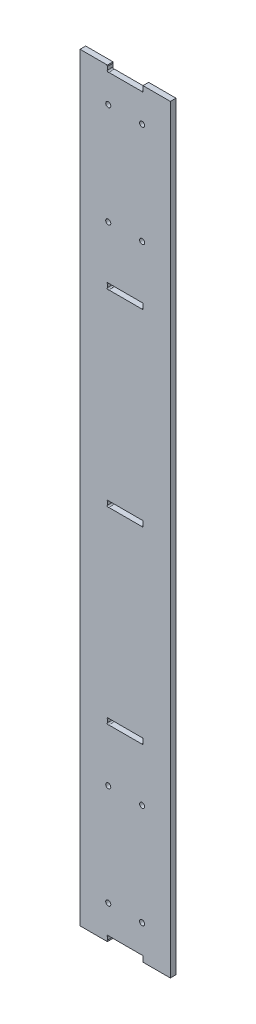
SolidWorks part; units mm, degrees
material "Acrylic (Medium-high impact)"
ref_plane "Front Plane" through (0, 0, 0) normal (0, 0, 1) x (1, 0, 0)
ref_plane "Top Plane" through (0, 0, 0) normal (0, 1, 0) x (1, 0, 0)
ref_plane "Right Plane" through (0, 0, 0) normal (1, 0, 0) x (0, 0, -1)
sketch "Sketch1" plane through (0, 0, 0) normal (0, 1, 0) x (1, 0, 0)
  line L0 (0, 0) -> (0, 76.2) construction
  line L2 (25.4, 68.667) -> (-25.4, 68.667)
  line L3 (25.4, 68.667) -> (25.4, 71.842)
  line L4 (25.4, 71.842) -> (-25.4, 71.842)
  line L5 (-25.4, 68.667) -> (-25.4, 71.842)
  line L6 (25.4, 68.667) -> (-25.4, 71.842) construction
  line L7 (25.4, 71.842) -> (-25.4, 68.667) construction
  circle A0 centre (0, 0) radius 76.2 construction
  point P4 (0, 70.2545)
  dimension "D1" = 152.4
  dimension "D2" = 3.175
  dimension "D3" = 50.8
extrude "Boss-Extrude1" add sketch "Sketch1" along normal blind 427.1518
sketch "Sketch2" plane through (0, 0, -68.667) normal (0, 0, 1) x (1, 0, 0)
  line L1 (-25.4, 427.1518) -> (25.4, 427.1518)
  line L2 (-25.4, 427.1518) -> (-25.4, 0)
  line L3 (-25.4, 0) -> (25.4, 0)
  line L4 (25.4, 427.1518) -> (25.4, 0)
sketch "Sketch3" plane through (0, 0, -68.667) normal (0, 0, 1) x (1, 0, 0)
  line L0 (0, 427.1518) -> (0, 0) construction
  line L1 (-25.4, 427.1518) -> (25.4, 427.1518) construction
  line L2 (-25.4, 0) -> (25.4, 0) construction
  line L3 (-25.4, 213.5759) -> (25.4, 213.5759) construction
  line L4 (-25.4, 427.1518) -> (-25.4, 0) construction
  line L5 (25.4, 427.1518) -> (25.4, 0) construction
  circle A0 centre (-19.05, 376.3518) radius 1.4224
  circle A1 centre (-12.7, 376.3518) radius 1.4224
  circle A2 centre (-6.35, 376.3518) radius 1.4224
  circle A3 centre (0, 376.3518) radius 1.4224
  circle A4 centre (6.35, 376.3518) radius 1.4224
  circle A5 centre (12.7, 376.3518) radius 1.4224
  circle A6 centre (19.05, 376.3518) radius 1.4224
  circle A7 centre (-12.7, 370.0018) radius 1.4224
  circle A8 centre (-6.35, 370.0018) radius 1.4224
  circle A9 centre (0, 370.0018) radius 1.4224
  circle A10 centre (6.35, 370.0018) radius 1.4224
  circle A11 centre (12.7, 370.0018) radius 1.4224
  circle A12 centre (19.05, 370.0018) radius 1.4224
  circle A13 centre (-12.7, 363.6518) radius 1.4224
  circle A14 centre (-6.35, 363.6518) radius 1.4224
  circle A15 centre (0, 363.6518) radius 1.4224
  circle A16 centre (6.35, 363.6518) radius 1.4224
  circle A17 centre (12.7, 363.6518) radius 1.4224
  circle A18 centre (19.05, 363.6518) radius 1.4224
  circle A19 centre (-12.7, 357.3018) radius 1.4224
  circle A20 centre (-6.35, 357.3018) radius 1.4224
  circle A21 centre (0, 357.3018) radius 1.4224
  circle A22 centre (6.35, 357.3018) radius 1.4224
  circle A23 centre (12.7, 357.3018) radius 1.4224
  circle A24 centre (19.05, 357.3018) radius 1.4224
  circle A25 centre (-12.7, 350.9518) radius 1.4224
  circle A26 centre (-6.35, 350.9518) radius 1.4224
  circle A27 centre (0, 350.9518) radius 1.4224
  circle A28 centre (6.35, 350.9518) radius 1.4224
  circle A29 centre (12.7, 350.9518) radius 1.4224
  circle A30 centre (19.05, 350.9518) radius 1.4224
  circle A31 centre (-12.7, 344.6018) radius 1.4224
  circle A32 centre (-6.35, 344.6018) radius 1.4224
  circle A33 centre (0, 344.6018) radius 1.4224
  circle A34 centre (6.35, 344.6018) radius 1.4224
  circle A35 centre (12.7, 344.6018) radius 1.4224
  circle A36 centre (19.05, 344.6018) radius 1.4224
  circle A37 centre (-12.7, 338.2518) radius 1.4224
  circle A38 centre (-6.35, 338.2518) radius 1.4224
  circle A39 centre (0, 338.2518) radius 1.4224
  circle A40 centre (6.35, 338.2518) radius 1.4224
  circle A41 centre (12.7, 338.2518) radius 1.4224
  circle A42 centre (19.05, 338.2518) radius 1.4224
  circle A43 centre (-12.7, 331.9018) radius 1.4224
  circle A44 centre (-6.35, 331.9018) radius 1.4224
  circle A45 centre (0, 331.9018) radius 1.4224
  circle A46 centre (6.35, 331.9018) radius 1.4224
  circle A47 centre (12.7, 331.9018) radius 1.4224
  circle A48 centre (19.05, 331.9018) radius 1.4224
  circle A49 centre (-19.05, 370.0018) radius 1.4224
  circle A50 centre (-19.05, 363.6518) radius 1.4224
  circle A51 centre (-19.05, 357.3018) radius 1.4224
  circle A52 centre (-19.05, 350.9518) radius 1.4224
  circle A53 centre (-19.05, 344.6018) radius 1.4224
  circle A54 centre (-19.05, 338.2518) radius 1.4224
  circle A55 centre (-19.05, 331.9018) radius 1.4224
  circle A56 centre (-19.05, 325.5518) radius 1.4224
  circle A57 centre (-12.7, 325.5518) radius 1.4224
  circle A58 centre (-6.35, 325.5518) radius 1.4224
  circle A59 centre (0, 325.5518) radius 1.4224
  circle A60 centre (6.35, 325.5518) radius 1.4224
  circle A61 centre (12.7, 325.5518) radius 1.4224
  circle A62 centre (19.05, 325.5518) radius 1.4224
  circle A63 centre (-19.05, 319.2018) radius 1.4224
  circle A64 centre (-12.7, 319.2018) radius 1.4224
  circle A65 centre (-6.35, 319.2018) radius 1.4224
  circle A66 centre (0, 319.2018) radius 1.4224
  circle A67 centre (6.35, 319.2018) radius 1.4224
  circle A68 centre (12.7, 319.2018) radius 1.4224
  circle A69 centre (19.05, 319.2018) radius 1.4224
  circle A70 centre (-19.05, 312.8518) radius 1.4224
  circle A71 centre (-12.7, 312.8518) radius 1.4224
  circle A72 centre (-6.35, 312.8518) radius 1.4224
  circle A73 centre (0, 312.8518) radius 1.4224
  circle A74 centre (6.35, 312.8518) radius 1.4224
  circle A75 centre (12.7, 312.8518) radius 1.4224
  circle A76 centre (19.05, 312.8518) radius 1.4224
  circle A77 centre (-19.05, 306.5018) radius 1.4224
  circle A78 centre (-12.7, 306.5018) radius 1.4224
  circle A79 centre (-6.35, 306.5018) radius 1.4224
  circle A80 centre (0, 306.5018) radius 1.4224
  circle A81 centre (6.35, 306.5018) radius 1.4224
  circle A82 centre (12.7, 306.5018) radius 1.4224
  circle A83 centre (19.05, 306.5018) radius 1.4224
  circle A84 centre (-19.05, 300.1518) radius 1.4224
  circle A85 centre (-12.7, 300.1518) radius 1.4224
  circle A86 centre (-6.35, 300.1518) radius 1.4224
  circle A87 centre (0, 300.1518) radius 1.4224
  circle A88 centre (6.35, 300.1518) radius 1.4224
  circle A89 centre (12.7, 300.1518) radius 1.4224
  circle A90 centre (19.05, 300.1518) radius 1.4224
  circle A91 centre (-19.05, 293.8018) radius 1.4224
  circle A92 centre (-12.7, 293.8018) radius 1.4224
  circle A93 centre (-6.35, 293.8018) radius 1.4224
  circle A94 centre (0, 293.8018) radius 1.4224
  circle A95 centre (6.35, 293.8018) radius 1.4224
  circle A96 centre (12.7, 293.8018) radius 1.4224
  circle A97 centre (19.05, 293.8018) radius 1.4224
  circle A98 centre (-19.05, 287.4518) radius 1.4224
  circle A99 centre (-12.7, 287.4518) radius 1.4224
  circle A100 centre (-6.35, 287.4518) radius 1.4224
  circle A101 centre (0, 287.4518) radius 1.4224
  circle A102 centre (6.35, 287.4518) radius 1.4224
  circle A103 centre (12.7, 287.4518) radius 1.4224
  circle A104 centre (19.05, 287.4518) radius 1.4224
  circle A105 centre (19.05, 139.7) radius 1.4224
  circle A106 centre (12.7, 139.7) radius 1.4224
  circle A107 centre (6.35, 139.7) radius 1.4224
  circle A108 centre (0, 139.7) radius 1.4224
  circle A109 centre (-6.35, 139.7) radius 1.4224
  circle A110 centre (-12.7, 139.7) radius 1.4224
  circle A111 centre (-19.05, 139.7) radius 1.4224
  circle A112 centre (19.05, 133.35) radius 1.4224
  circle A113 centre (12.7, 133.35) radius 1.4224
  circle A114 centre (6.35, 133.35) radius 1.4224
  circle A115 centre (0, 133.35) radius 1.4224
  circle A116 centre (-6.35, 133.35) radius 1.4224
  circle A117 centre (-12.7, 133.35) radius 1.4224
  circle A118 centre (-19.05, 133.35) radius 1.4224
  circle A119 centre (19.05, 127) radius 1.4224
  circle A120 centre (12.7, 127) radius 1.4224
  circle A121 centre (6.35, 127) radius 1.4224
  circle A122 centre (0, 127) radius 1.4224
  circle A123 centre (-6.35, 127) radius 1.4224
  circle A124 centre (-12.7, 127) radius 1.4224
  circle A125 centre (-19.05, 127) radius 1.4224
  circle A126 centre (19.05, 120.65) radius 1.4224
  circle A127 centre (12.7, 120.65) radius 1.4224
  circle A128 centre (6.35, 120.65) radius 1.4224
  circle A129 centre (0, 120.65) radius 1.4224
  circle A130 centre (-6.35, 120.65) radius 1.4224
  circle A131 centre (-12.7, 120.65) radius 1.4224
  circle A132 centre (-19.05, 120.65) radius 1.4224
  circle A133 centre (19.05, 114.3) radius 1.4224
  circle A134 centre (12.7, 114.3) radius 1.4224
  circle A135 centre (6.35, 114.3) radius 1.4224
  circle A136 centre (0, 114.3) radius 1.4224
  circle A137 centre (-6.35, 114.3) radius 1.4224
  circle A138 centre (-12.7, 114.3) radius 1.4224
  circle A139 centre (-19.05, 114.3) radius 1.4224
  circle A140 centre (19.05, 107.95) radius 1.4224
  circle A141 centre (12.7, 107.95) radius 1.4224
  circle A142 centre (6.35, 107.95) radius 1.4224
  circle A143 centre (0, 107.95) radius 1.4224
  circle A144 centre (-6.35, 107.95) radius 1.4224
  circle A145 centre (-12.7, 107.95) radius 1.4224
  circle A146 centre (-19.05, 107.95) radius 1.4224
  circle A147 centre (19.05, 101.6) radius 1.4224
  circle A148 centre (12.7, 101.6) radius 1.4224
  circle A149 centre (6.35, 101.6) radius 1.4224
  circle A150 centre (0, 101.6) radius 1.4224
  circle A151 centre (-6.35, 101.6) radius 1.4224
  circle A152 centre (-12.7, 101.6) radius 1.4224
  circle A153 centre (-19.05, 101.6) radius 1.4224
  circle A154 centre (-19.05, 95.25) radius 1.4224
  circle A155 centre (-19.05, 88.9) radius 1.4224
  circle A156 centre (-19.05, 82.55) radius 1.4224
  circle A157 centre (-19.05, 76.2) radius 1.4224
  circle A158 centre (-19.05, 69.85) radius 1.4224
  circle A159 centre (-19.05, 63.5) radius 1.4224
  circle A160 centre (-19.05, 57.15) radius 1.4224
  circle A161 centre (19.05, 95.25) radius 1.4224
  circle A162 centre (12.7, 95.25) radius 1.4224
  circle A163 centre (6.35, 95.25) radius 1.4224
  circle A164 centre (0, 95.25) radius 1.4224
  circle A165 centre (-6.35, 95.25) radius 1.4224
  circle A166 centre (-12.7, 95.25) radius 1.4224
  circle A167 centre (19.05, 88.9) radius 1.4224
  circle A168 centre (12.7, 88.9) radius 1.4224
  circle A169 centre (6.35, 88.9) radius 1.4224
  circle A170 centre (0, 88.9) radius 1.4224
  circle A171 centre (-6.35, 88.9) radius 1.4224
  circle A172 centre (-12.7, 88.9) radius 1.4224
  circle A173 centre (19.05, 82.55) radius 1.4224
  circle A174 centre (12.7, 82.55) radius 1.4224
  circle A175 centre (6.35, 82.55) radius 1.4224
  circle A176 centre (0, 82.55) radius 1.4224
  circle A177 centre (-6.35, 82.55) radius 1.4224
  circle A178 centre (-12.7, 82.55) radius 1.4224
  circle A179 centre (19.05, 76.2) radius 1.4224
  circle A180 centre (12.7, 76.2) radius 1.4224
  circle A181 centre (6.35, 76.2) radius 1.4224
  circle A182 centre (0, 76.2) radius 1.4224
  circle A183 centre (-6.35, 76.2) radius 1.4224
  circle A184 centre (-12.7, 76.2) radius 1.4224
  circle A185 centre (19.05, 69.85) radius 1.4224
  circle A186 centre (12.7, 69.85) radius 1.4224
  circle A187 centre (6.35, 69.85) radius 1.4224
  circle A188 centre (0, 69.85) radius 1.4224
  circle A189 centre (-6.35, 69.85) radius 1.4224
  circle A190 centre (-12.7, 69.85) radius 1.4224
  circle A191 centre (19.05, 63.5) radius 1.4224
  circle A192 centre (12.7, 63.5) radius 1.4224
  circle A193 centre (6.35, 63.5) radius 1.4224
  circle A194 centre (0, 63.5) radius 1.4224
  circle A195 centre (-6.35, 63.5) radius 1.4224
  circle A196 centre (-12.7, 63.5) radius 1.4224
  circle A197 centre (19.05, 57.15) radius 1.4224
  circle A198 centre (12.7, 57.15) radius 1.4224
  circle A199 centre (6.35, 57.15) radius 1.4224
  circle A200 centre (0, 57.15) radius 1.4224
  circle A201 centre (-6.35, 57.15) radius 1.4224
  circle A202 centre (-12.7, 57.15) radius 1.4224
  circle A203 centre (19.05, 50.8) radius 1.4224
  circle A204 centre (12.7, 50.8) radius 1.4224
  circle A205 centre (6.35, 50.8) radius 1.4224
  circle A206 centre (0, 50.8) radius 1.4224
  circle A207 centre (-6.35, 50.8) radius 1.4224
  circle A208 centre (-12.7, 50.8) radius 1.4224
  circle A209 centre (-19.05, 50.8) radius 1.4224
  dimension "D1" = 2.8448
  dimension "D2" = 6.35
  dimension "D3" = 50.8
  dimension "D4" = 7
  dimension "D5" = 8
  dimension "D6" = 8
sketch "Sketch4" plane through (0, 0, -68.667) normal (0, 0, 1) x (1, 0, 0)
  line L0 (0, 427.1518) -> (0, 0) construction
  line L1 (-25.4, 427.1518) -> (25.4, 427.1518) construction
  line L2 (-25.4, 0) -> (25.4, 0) construction
  circle A0 centre (-3.175, 376.3518) radius 1.4224
  circle A2 centre (-9.525, 376.3518) radius 1.4224
  circle A4 centre (-9.525, 370.0018) radius 1.4224
  circle A6 centre (-9.525, 363.6518) radius 1.4224
  circle A8 centre (-9.525, 357.3018) radius 1.4224
  circle A10 centre (-9.525, 350.9518) radius 1.4224
  circle A12 centre (-9.525, 344.6018) radius 1.4224
  circle A14 centre (-9.525, 338.2518) radius 1.4224
  circle A16 centre (-9.525, 331.9018) radius 1.4224
  circle A18 centre (-9.525, 325.5518) radius 1.4224
  circle A20 centre (-9.525, 319.2018) radius 1.4224
  circle A22 centre (-9.525, 312.8518) radius 1.4224
  circle A24 centre (-9.525, 306.5018) radius 1.4224
  circle A26 centre (-9.525, 300.1518) radius 1.4224
  circle A28 centre (-9.525, 293.8018) radius 1.4224
  circle A30 centre (-9.525, 287.4518) radius 1.4224
  circle A32 centre (-9.525, 281.1018) radius 1.4224
  circle A34 centre (-3.175, 370.0018) radius 1.4224
  circle A35 centre (-3.175, 363.6518) radius 1.4224
  circle A36 centre (-3.175, 357.3018) radius 1.4224
  circle A37 centre (-3.175, 350.9518) radius 1.4224
  circle A38 centre (-3.175, 344.6018) radius 1.4224
  circle A39 centre (-3.175, 338.2518) radius 1.4224
  circle A40 centre (-3.175, 331.9018) radius 1.4224
  circle A41 centre (-3.175, 325.5518) radius 1.4224
  circle A42 centre (-3.175, 319.2018) radius 1.4224
  circle A43 centre (-3.175, 312.8518) radius 1.4224
  circle A44 centre (-3.175, 306.5018) radius 1.4224
  circle A45 centre (-3.175, 300.1518) radius 1.4224
  circle A46 centre (-3.175, 293.8018) radius 1.4224
  circle A47 centre (-3.175, 287.4518) radius 1.4224
  circle A48 centre (-3.175, 281.1018) radius 1.4224
  circle A49 centre (3.175, 281.1018) radius 1.4224
  circle A50 centre (3.175, 287.4518) radius 1.4224
  circle A51 centre (3.175, 293.8018) radius 1.4224
  circle A52 centre (3.175, 300.1518) radius 1.4224
  circle A53 centre (3.175, 306.5018) radius 1.4224
  circle A54 centre (3.175, 312.8518) radius 1.4224
  circle A55 centre (3.175, 319.2018) radius 1.4224
  circle A56 centre (3.175, 325.5518) radius 1.4224
  circle A57 centre (3.175, 331.9018) radius 1.4224
  circle A58 centre (3.175, 338.2518) radius 1.4224
  circle A59 centre (3.175, 344.6018) radius 1.4224
  circle A60 centre (3.175, 350.9518) radius 1.4224
  circle A61 centre (3.175, 357.3018) radius 1.4224
  circle A62 centre (3.175, 363.6518) radius 1.4224
  circle A63 centre (3.175, 370.0018) radius 1.4224
  circle A65 centre (9.525, 281.1018) radius 1.4224
  circle A67 centre (9.525, 287.4518) radius 1.4224
  circle A69 centre (9.525, 293.8018) radius 1.4224
  circle A71 centre (9.525, 300.1518) radius 1.4224
  circle A73 centre (9.525, 306.5018) radius 1.4224
  circle A75 centre (9.525, 312.8518) radius 1.4224
  circle A77 centre (9.525, 319.2018) radius 1.4224
  circle A79 centre (9.525, 325.5518) radius 1.4224
  circle A81 centre (9.525, 331.9018) radius 1.4224
  circle A83 centre (9.525, 338.2518) radius 1.4224
  circle A85 centre (9.525, 344.6018) radius 1.4224
  circle A87 centre (9.525, 350.9518) radius 1.4224
  circle A89 centre (9.525, 357.3018) radius 1.4224
  circle A91 centre (9.525, 363.6518) radius 1.4224
  circle A93 centre (9.525, 370.0018) radius 1.4224
  circle A95 centre (9.525, 376.3518) radius 1.4224
  circle A96 centre (3.175, 376.3518) radius 1.4224
  circle A97 centre (-9.525, 382.7018) radius 1.4224
  circle A100 centre (9.525, 382.7018) radius 1.4224
  circle A103 centre (-9.525, 389.0518) radius 1.4224
  circle A106 centre (9.525, 389.0518) radius 1.4224
  circle A109 centre (-9.525, 395.4018) radius 1.4224
  circle A112 centre (9.525, 395.4018) radius 1.4224
  circle A115 centre (-9.525, 401.7518) radius 1.4224
  circle A118 centre (9.525, 401.7518) radius 1.4224
  circle A121 centre (-9.525, 408.1018) radius 1.4224
  circle A124 centre (9.525, 408.1018) radius 1.4224
  circle A127 centre (-9.525, 414.4518) radius 1.4224
  circle A130 centre (9.525, 414.4518) radius 1.4224
  circle A144 centre (-3.175, 382.7018) radius 1.4224 [skipped]
  circle A145 centre (-3.175, 389.0518) radius 1.4224 [skipped]
  circle A146 centre (-3.175, 395.4018) radius 1.4224 [skipped]
  circle A147 centre (-3.175, 401.7518) radius 1.4224 [skipped]
  circle A148 centre (-3.175, 408.1018) radius 1.4224 [skipped]
  circle A149 centre (-3.175, 414.4518) radius 1.4224 [skipped]
  circle A150 centre (3.175, 382.7018) radius 1.4224 [skipped]
  circle A151 centre (3.175, 389.0518) radius 1.4224 [skipped]
  circle A152 centre (3.175, 395.4018) radius 1.4224 [skipped]
  circle A153 centre (3.175, 401.7518) radius 1.4224 [skipped]
  circle A154 centre (3.175, 408.1018) radius 1.4224 [skipped]
  circle A155 centre (3.175, 414.4518) radius 1.4224 [skipped]
  circle A156 centre (-15.875, 363.6518) radius 1.4224 [skipped]
  circle A157 centre (-15.875, 357.3018) radius 1.4224 [skipped]
  circle A158 centre (-15.875, 350.9518) radius 1.4224 [skipped]
  circle A159 centre (-15.875, 344.6018) radius 1.4224 [skipped]
  circle A160 centre (-15.875, 338.2518) radius 1.4224 [skipped]
  circle A161 centre (-15.875, 331.9018) radius 1.4224 [skipped]
  circle A162 centre (-15.875, 325.5518) radius 1.4224 [skipped]
  circle A163 centre (-15.875, 319.2018) radius 1.4224 [skipped]
  circle A164 centre (-15.875, 312.8518) radius 1.4224 [skipped]
  circle A165 centre (-15.875, 306.5018) radius 1.4224 [skipped]
  circle A166 centre (-15.875, 300.1518) radius 1.4224 [skipped]
  circle A167 centre (-15.875, 293.8018) radius 1.4224 [skipped]
  circle A168 centre (-15.875, 287.4518) radius 1.4224 [skipped]
  circle A169 centre (-15.875, 281.1018) radius 1.4224 [skipped]
  circle A170 centre (-15.875, 376.3518) radius 1.4224 [skipped]
  circle A171 centre (-15.875, 370.0018) radius 1.4224 [skipped]
  dimension "D2" = 2.8448
  dimension "D1" = 3.175
  dimension "D3" = 50.8
  dimension "D4" = 3
  dimension "D5" = 16
  dimension "D7" = 7
extrude "Cut-Extrude2" cut sketch "Sketch4" against normal blind 5.08
sketch "Sketch5" plane through (0, 0, -68.667) normal (0, 0, 1) x (1, 0, 0)
  line L1 (-6.4666, 378.8778) -> (6.1161, 378.8778)
  line L2 (-6.4666, 378.8778) -> (-6.4666, 277.848)
  line L3 (-6.4666, 277.848) -> (6.1161, 277.848)
  line L4 (6.1161, 378.8778) -> (6.1161, 277.848)
extrude "Boss-Extrude2" add sketch "Sketch5" against normal blind 3.175
sketch "Sketch6" plane through (0, 0, -68.667) normal (0, 0, 1) x (1, 0, 0)
  line L1 (-20.2574, 381.0412) -> (-12.7108, 381.0412)
  line L2 (-20.2574, 381.0412) -> (-20.2574, 272.3701)
  line L3 (-20.2574, 272.3701) -> (-12.7108, 272.3701)
  line L4 (-12.7108, 381.0412) -> (-12.7108, 272.3701)
  line L5 (12.4446, 381.0412) -> (21.5005, 381.0412)
  line L6 (12.4446, 381.0412) -> (12.4446, 272.3701)
  line L7 (12.4446, 272.3701) -> (21.5005, 272.3701)
  line L8 (21.5005, 381.0412) -> (21.5005, 272.3701)
extrude "Boss-Extrude3" add sketch "Sketch6" against normal blind 3.175
sketch "Sketch7" plane through (0, 0, -68.667) normal (0, 0, 1) x (1, 0, 0)
  line L0 (25.4, 427.1518) -> (25.4, 0) construction
  line L1 (-25.4, 427.1518) -> (25.4, 427.1518)
  line L2 (-25.4, 427.1518) -> (-25.4, 410.6418)
  line L3 (-25.4, 410.6418) -> (25.4, 410.6418)
  line L4 (25.4, 427.1518) -> (25.4, 410.6418)
  dimension "D1" = 16.51
extrude "Boss-Extrude4" add sketch "Sketch7" against normal blind 3.175
sketch "Sketch8" plane through (0, 0, -68.667) normal (0, 0, 1) x (1, 0, 0)
  line L0 (-25.4, 427.1518) -> (-25.4, 0) construction
  line L1 (-25.4, 404.9269) -> (25.4, 404.9269)
  line L2 (-25.4, 404.9269) -> (-25.4, 353.7389)
  line L3 (-25.4, 353.7389) -> (25.4, 353.7389)
  line L4 (25.4, 404.9269) -> (25.4, 353.7389)
  line L5 (25.4, 427.1518) -> (25.4, 0) construction
extrude "Boss-Extrude5" add sketch "Sketch8" against normal blind 3.175
sketch "Sketch9" plane through (0, 0, -68.667) normal (0, 0, 1) x (1, 0, 0)
  line L0 (-25.4, 427.1518) -> (-25.4, 0) construction
  line L1 (-25.4, 347.6) -> (25.4, 347.6)
  line L2 (-25.4, 347.6) -> (-25.4, 277.4309)
  line L3 (-25.4, 277.4309) -> (25.4, 277.4309)
  line L4 (25.4, 347.6) -> (25.4, 277.4309)
  line L5 (25.4, 427.1518) -> (25.4, 0) construction
extrude "Boss-Extrude6" add sketch "Sketch9" against normal blind 3.175
sketch "Sketch10" plane through (0, 0, -68.667) normal (0, 0, 1) x (1, 0, 0)
  line L0 (-25.4, 213.5759) -> (25.4, 213.5759) construction
  line L1 (-25.4, 427.1518) -> (-25.4, 0) construction
  line L2 (25.4, 427.1518) -> (25.4, 0) construction
ref_plane "Plane1" through (0, 213.5759, 0) normal (0, 1, 0) x (1, 0, 0)
mirror "Mirror1" about plane through (0, 213.5759, 0) normal (0, 1, 0) of "Boss-Extrude4", "Boss-Extrude6", "Boss-Extrude5", "Boss-Extrude3", "Boss-Extrude2", "Cut-Extrude2"
sketch "Sketch11" plane through (0, 0, -68.667) normal (0, 0, 1) x (1, 0, 0)
  line L0 (25.4, 0) -> (-25.4, 0) construction
  line L1 (-25.4, 213.5759) -> (25.4, 213.5759) construction
  line L2 (-25.4, 427.1518) -> (-25.4, 0) construction
  line L3 (25.4, 427.1518) -> (25.4, 0) construction
  line L4 (-9.6464, 2.8214) -> (9.6464, 0.3536) construction
  line L5 (9.2929, 105.9942) -> (-9.2929, 105.9942)
  line L6 (10, 106.7013) -> (10, 108.4621)
  line L7 (9.2929, 109.1692) -> (-9.2929, 109.1692)
  line L8 (10, 3.175) -> (10, 2.4679) construction
  line L9 (9.2929, 0) -> (-9.2929, 0)
  line L10 (10, 0.7071) -> (10, 2.4679)
  line L11 (9.2929, 3.175) -> (-9.2929, 3.175)
  line L12 (-10, 0.7071) -> (-10, 2.4679)
  line L13 (10, 3.175) -> (9.2929, 3.175) construction
  line L14 (10, 0.7071) -> (10, 0) construction
  line L15 (10, 0) -> (9.2929, 0) construction
  line L16 (-9.2929, 0) -> (-10, 0) construction
  line L17 (-10, 0) -> (-10, 0.7071) construction
  line L18 (-10, 2.4679) -> (-10, 3.175) construction
  line L19 (-10, 3.175) -> (-9.2929, 3.175) construction
  line L20 (-25.4, 0) -> (25.4, 0) construction
  line L21 (-10, 106.7013) -> (-10, 108.4621)
  line L22 (-9.6464, 108.8156) -> (9.6464, 106.3478) construction
  line L23 (10, 109.1692) -> (10, 108.4621) construction
  line L24 (10, 109.1692) -> (9.2929, 109.1692) construction
  line L25 (10, 106.7013) -> (10, 105.9942) construction
  line L26 (10, 105.9942) -> (9.2929, 105.9942) construction
  line L27 (-9.2929, 105.9942) -> (-10, 105.9942) construction
  line L28 (-10, 105.9942) -> (-10, 106.7013) construction
  line L29 (-10, 108.4621) -> (-10, 109.1692) construction
  line L30 (-10, 109.1692) -> (-9.2929, 109.1692) construction
  line L31 (9.2929, 211.9884) -> (-9.2929, 211.9884)
  line L32 (10, 212.6955) -> (10, 214.4563)
  line L33 (9.2929, 215.1634) -> (-9.2929, 215.1634)
  line L34 (-10, 212.6955) -> (-10, 214.4563)
  line L35 (-9.6464, 214.8098) -> (9.6464, 212.342) construction
  line L36 (10, 215.1634) -> (10, 214.4563) construction
  line L37 (10, 215.1634) -> (9.2929, 215.1634) construction
  line L38 (10, 212.6955) -> (10, 211.9884) construction
  line L39 (10, 211.9884) -> (9.2929, 211.9884) construction
  line L40 (-9.2929, 211.9884) -> (-10, 211.9884) construction
  line L41 (-10, 211.9884) -> (-10, 212.6955) construction
  line L42 (-10, 214.4563) -> (-10, 215.1634) construction
  line L43 (-10, 215.1634) -> (-9.2929, 215.1634) construction
  arc A0 (10, 2.4679) -> (9.2929, 3.175) centre (9.6464, 2.8214) ccw
  arc A1 (10, 0.7071) -> (9.2929, 0) centre (9.6464, 0.3536) cw
  arc A2 (-9.2929, 0) -> (-10, 0.7071) centre (-9.6464, 0.3536) cw
  arc A3 (-10, 2.4679) -> (-9.2929, 3.175) centre (-9.6464, 2.8214) cw
  arc A4 (10, 108.4621) -> (9.2929, 109.1692) centre (9.6464, 108.8156) ccw
  arc A5 (10, 106.7013) -> (9.2929, 105.9942) centre (9.6464, 106.3478) cw
  arc A6 (-9.2929, 105.9942) -> (-10, 106.7013) centre (-9.6464, 106.3478) cw
  arc A7 (-10, 108.4621) -> (-9.2929, 109.1692) centre (-9.6464, 108.8156) cw
  arc A8 (10, 214.4563) -> (9.2929, 215.1634) centre (9.6464, 214.8098) ccw
  arc A9 (10, 212.6955) -> (9.2929, 211.9884) centre (9.6464, 212.342) cw
  arc A10 (-9.2929, 211.9884) -> (-10, 212.6955) centre (-9.6464, 212.342) cw
  arc A11 (-10, 214.4563) -> (-9.2929, 215.1634) centre (-9.6464, 214.8098) cw
  point P2 (0, 0)
  point P3 (0, 0)
  point P11 (0, 213.5759)
  point P29 (-25.4, 213.5759)
  point P32 (25.4, 213.5759)
  point P63 (0, 213.5759)
  dimension "D1" = 0.5
  dimension "D2" = 20
  dimension "D4" = 3.175
  dimension "D3" = 3
extrude "Cut-Extrude3" cut sketch "Sketch11" against normal through all
ref_plane "Plane2" through (0, 213.5759, 0) normal (0, -1, 0) x (-1, 0, 0)
mirror "Mirror2" about plane through (0, 213.5759, 0) normal (0, -1, 0) of "Cut-Extrude3"
hole_wizard "#4 Clearance Hole1" positions "Sketch13" profile "Sketch14" hole size "#4" standard "ANSI Inch"
sketch "Sketch13" plane through (0, 0, -68.667) normal (0, 0, 1) x (1, 0, 0)
  line L1 (9.2929, 215.1634) -> (-9.2929, 215.1634) construction
  line L2 (0, 215.1634) -> (0, 220.853) construction
  line L4 (-20.32, 220.853) -> (-20.32, 231.013) construction
  line L6 (-20.32, 220.853) -> (-10.16, 220.853) construction
  line L9 (0, 317.9826) -> (0, 312.293) construction
  line L10 (9.2929, 317.9826) -> (-9.2929, 317.9826) construction
  line L12 (-25.4, 213.5759) -> (25.4, 213.5759) construction
  line L13 (-25.4, 427.1518) -> (-25.4, 0) construction
  line L15 (25.4, 427.1518) -> (25.4, 0) construction
  point P0 (-20.32, 220.853)
  point P18 (-10.16, 220.853)
  point P19 (0, 220.853)
  point P20 (10.16, 220.853)
  point P21 (20.32, 220.853)
  point P22 (-10.16, 231.013)
  point P23 (0, 231.013)
  point P24 (10.16, 231.013)
  point P25 (20.32, 231.013)
  point P26 (-10.16, 241.173)
  point P27 (0, 241.173)
  point P28 (10.16, 241.173)
  point P29 (20.32, 241.173)
  point P30 (-10.16, 251.333)
  point P31 (0, 251.333)
  point P32 (10.16, 251.333)
  point P33 (20.32, 251.333)
  point P34 (-10.16, 261.493)
  point P35 (0, 261.493)
  point P36 (10.16, 261.493)
  point P37 (20.32, 261.493)
  point P38 (-10.16, 271.653)
  point P39 (0, 271.653)
  point P40 (10.16, 271.653)
  point P41 (20.32, 271.653)
  point P42 (-10.16, 281.813)
  point P43 (0, 281.813)
  point P44 (10.16, 281.813)
  point P45 (20.32, 281.813)
  point P46 (-10.16, 291.973)
  point P47 (0, 291.973)
  point P48 (10.16, 291.973)
  point P49 (20.32, 291.973)
  point P50 (-10.16, 302.133)
  point P51 (0, 302.133)
  point P52 (10.16, 302.133)
  point P53 (20.32, 302.133)
  point P54 (-10.16, 312.293)
  point P55 (0, 312.293)
  point P56 (10.16, 312.293)
  point P57 (20.32, 312.293)
  point P58 (-20.32, 231.013)
  point P59 (-20.32, 241.173)
  point P60 (-20.32, 251.333)
  point P61 (-20.32, 261.493)
  point P62 (-20.32, 271.653)
  point P63 (-20.32, 281.813)
  point P64 (-20.32, 291.973)
  point P65 (-20.32, 302.133)
  point P66 (-20.32, 312.293)
  point P98 (-20.32, 114.8588)
  point P99 (-20.32, 125.0188)
  point P100 (-20.32, 135.1788)
  point P101 (-20.32, 145.3388)
  point P102 (-20.32, 155.4988)
  point P103 (-20.32, 165.6588)
  point P104 (-20.32, 175.8188)
  point P105 (-20.32, 185.9788)
  point P106 (-20.32, 196.1388)
  point P107 (20.32, 114.8588)
  point P108 (10.16, 114.8588)
  point P109 (0, 114.8588)
  point P110 (-10.16, 114.8588)
  point P111 (20.32, 125.0188)
  point P112 (10.16, 125.0188)
  point P113 (0, 125.0188)
  point P114 (-10.16, 125.0188)
  point P115 (20.32, 135.1788)
  point P116 (10.16, 135.1788)
  point P117 (0, 135.1788)
  point P118 (-10.16, 135.1788)
  point P119 (20.32, 145.3388)
  point P120 (10.16, 145.3388)
  point P121 (0, 145.3388)
  point P122 (-10.16, 145.3388)
  point P123 (20.32, 155.4988)
  point P124 (10.16, 155.4988)
  point P125 (0, 155.4988)
  point P126 (-10.16, 155.4988)
  point P127 (20.32, 165.6588)
  point P128 (10.16, 165.6588)
  point P129 (0, 165.6588)
  point P130 (-10.16, 165.6588)
  point P131 (20.32, 175.8188)
  point P132 (10.16, 175.8188)
  point P133 (0, 175.8188)
  point P134 (-10.16, 175.8188)
  point P135 (20.32, 185.9788)
  point P136 (10.16, 185.9788)
  point P137 (0, 185.9788)
  point P138 (-10.16, 185.9788)
  point P139 (20.32, 196.1388)
  point P140 (10.16, 196.1388)
  point P141 (0, 196.1388)
  point P142 (-10.16, 196.1388)
  point P143 (20.32, 206.2988)
  point P144 (10.16, 206.2988)
  point P145 (0, 206.2988)
  point P146 (-10.16, 206.2988)
  point P147 (-20.32, 206.2988)
  dimension "D1" = 10.16
  dimension "D5" = 10.16
  dimension "D3" = 5
  dimension "D4" = 10
sketch "Sketch14" plane through (-20.32, 220.853, -68.667) normal (1, 0, 0) x (0, -1, 0)
  line L0 (0, 0) -> (0, 3.175)
  line L1 (0, 3.175) -> (1.6319, 3.175)
  line L2 (1.6319, 3.175) -> (1.6319, 0)
  line L5 (1.6319, 0) -> (0, 0)
  line L11 (0, -6.35) -> (0, 107.95) construction
  dimension "Thru Hole Dia." = 3.2639
  dimension "Thru Hole Depth" = 3.175
hole_wizard "#4 Clearance Hole2" positions "Sketch15" profile "Sketch16" hole size "#4" standard "ANSI Inch"
sketch "Sketch15" plane through (0, 0, -68.667) normal (0, 0, 1) x (1, 0, 0)
  line L2 (-20.32, 399.8468) -> (-10.16, 399.8468) construction
  line L4 (-20.32, 399.8468) -> (-20.32, 389.6868) construction
  line L6 (-9.525, 408.1018) -> (9.525, 408.1018) construction
  line L8 (0, 408.1018) -> (0, 399.8468) construction
  line L10 (-9.525, 350.9518) -> (9.525, 350.9518) construction
  line L12 (0, 350.9518) -> (0, 359.2068) construction
  line L14 (-25.4, 213.5759) -> (25.4, 213.5759) construction
  line L15 (-25.4, 427.1518) -> (-25.4, 0) construction
  line L16 (25.4, 427.1518) -> (25.4, 0) construction
  line L18 (-20.32, 336.0547) -> (-20.32, 346.2147) construction
  line L19 (-20.32, 346.2147) -> (-10.16, 346.2147) construction
  line L21 (0, 346.2147) -> (0, 350.9518) construction
  line L23 (0, 321.1576) -> (0, 325.8947) construction
  line L24 (-9.2929, 321.1576) -> (9.2929, 321.1576) construction
  point P0 (-20.32, 399.8468)
  point P8 (-10.16, 399.8468)
  point P9 (0, 399.8468)
  point P10 (10.16, 399.8468)
  point P11 (20.32, 399.8468)
  point P12 (-10.16, 389.6868)
  point P13 (0, 389.6868)
  point P14 (10.16, 389.6868)
  point P15 (20.32, 389.6868)
  point P16 (-10.16, 379.5268)
  point P17 (0, 379.5268)
  point P18 (10.16, 379.5268)
  point P19 (20.32, 379.5268)
  point P20 (-10.16, 369.3668)
  point P21 (0, 369.3668)
  point P22 (10.16, 369.3668)
  point P23 (20.32, 369.3668)
  point P24 (-10.16, 359.2068)
  point P25 (0, 359.2068)
  point P26 (10.16, 359.2068)
  point P27 (20.32, 359.2068)
  point P28 (-20.32, 389.6868)
  point P29 (-20.32, 379.5268)
  point P30 (-20.32, 369.3668)
  point P31 (-20.32, 359.2068)
  point P73 (-20.32, 67.945)
  point P74 (-20.32, 57.785)
  point P75 (-20.32, 47.625)
  point P76 (-20.32, 37.465)
  point P77 (20.32, 67.945)
  point P78 (10.16, 67.945)
  point P79 (0, 67.945)
  point P80 (-10.16, 67.945)
  point P81 (20.32, 57.785)
  point P82 (10.16, 57.785)
  point P83 (0, 57.785)
  point P84 (-10.16, 57.785)
  point P85 (20.32, 47.625)
  point P86 (10.16, 47.625)
  point P87 (0, 47.625)
  point P88 (-10.16, 47.625)
  point P89 (20.32, 37.465)
  point P90 (10.16, 37.465)
  point P91 (0, 37.465)
  point P92 (-10.16, 37.465)
  point P93 (20.32, 27.305)
  point P94 (10.16, 27.305)
  point P95 (0, 27.305)
  point P96 (-10.16, 27.305)
  point P97 (-20.32, 27.305)
  point P98 (-20.32, 346.2147)
  point P105 (-10.16, 346.2147)
  point P106 (0, 346.2147)
  point P107 (10.16, 346.2147)
  point P108 (20.32, 346.2147)
  point P109 (-10.16, 336.0547)
  point P110 (0, 336.0547)
  point P111 (10.16, 336.0547)
  point P112 (20.32, 336.0547)
  point P113 (-10.16, 325.8947)
  point P114 (0, 325.8947)
  point P115 (10.16, 325.8947)
  point P116 (20.32, 325.8947)
  point P117 (-20.32, 336.0547)
  point P118 (-20.32, 325.8947)
  point P134 (-20.32, 101.2571)
  point P135 (-20.32, 91.0971)
  point P136 (20.32, 101.2571)
  point P137 (10.16, 101.2571)
  point P138 (0, 101.2571)
  point P139 (-10.16, 101.2571)
  point P140 (20.32, 91.0971)
  point P141 (10.16, 91.0971)
  point P142 (0, 91.0971)
  point P143 (-10.16, 91.0971)
  point P144 (20.32, 80.9371)
  point P145 (10.16, 80.9371)
  point P146 (0, 80.9371)
  point P147 (-10.16, 80.9371)
  point P148 (-20.32, 80.9371)
  dimension "D3" = 10.16
  dimension "D4" = 10.16
  dimension "D7" = 10.16
  dimension "D8" = 10.16
  dimension "D1" = 5
  dimension "D2" = 5
  dimension "D5" = 5
  dimension "D6" = 3
sketch "Sketch16" plane through (-20.32, 399.8468, -68.667) normal (1, 0, 0) x (0, -1, 0)
  line L0 (0, 0) -> (0, 3.175)
  line L1 (0, 3.175) -> (1.6319, 3.175)
  line L2 (1.6319, 3.175) -> (1.6319, 0)
  line L5 (1.6319, 0) -> (0, 0)
  line L11 (0, -6.35) -> (0, 107.95) construction
  dimension "Thru Hole Dia." = 3.2639
  dimension "Thru Hole Depth" = 3.175
sketch "timestamp" plane through (0, 0, -71.842) normal (0, 0, -1) x (-1, 0, 0)
  line L0 (-17.7, 201.2657) -> (-17.7, 225.8861) construction
  line L1 (-10, 212.6955) -> (-10, 214.4563) construction
  line L2 (-10, 213.5759) -> (-25.4, 213.5759) construction
  line L3 (-25.4, 427.1518) -> (-25.4, 0) construction
  text T0 "11/3/2017"
  point P3 (-17.7, 213.5759)
  point P4 (-17.7, 213.5759)
  point P11 (-17.7, 171.878)
  point P12 (-17.7, 201.2657)
